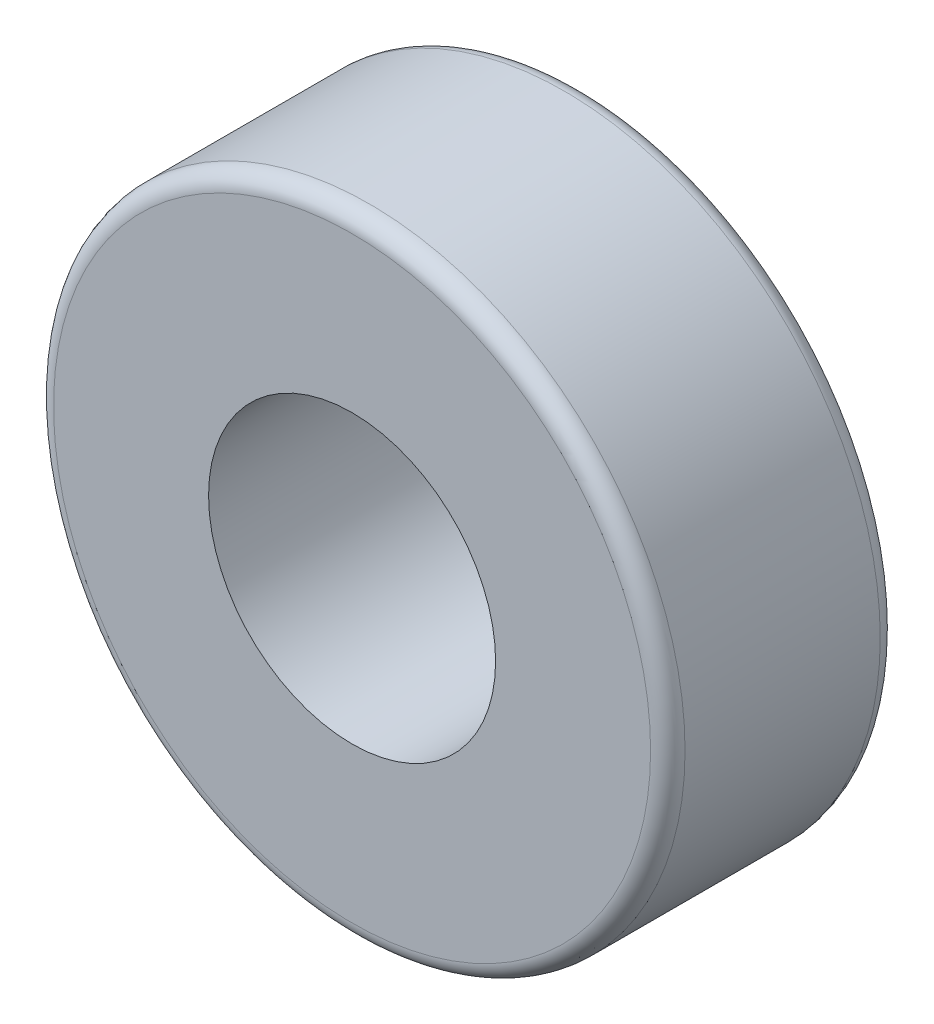
SolidWorks part; units mm, degrees
material "Plain Carbon Steel"
ref_plane "Front Plane" through (0, 0, 0) normal (0, 0, 1) x (1, 0, 0)
ref_plane "Top Plane" through (0, 0, 0) normal (0, 1, 0) x (1, 0, 0)
ref_plane "Right Plane" through (0, 0, 0) normal (1, 0, 0) x (0, 0, -1)
sketch "Sketch1" plane through (0, 0, 0) normal (0, 0, 1) x (1, 0, 0)
  circle A0 centre (0, 0) radius 5.5
  circle A1 centre (0, 0) radius 2.5
  dimension "D1" = 5
  dimension "D2" = 11
extrude "Boss-Extrude1" add sketch "Sketch1" along normal mid plane 4
fillet "Fillet2" radius 0.3 3 edges at (5.5, 0, 2) (5.5, 0, -2) (2.5, 0, -2)
